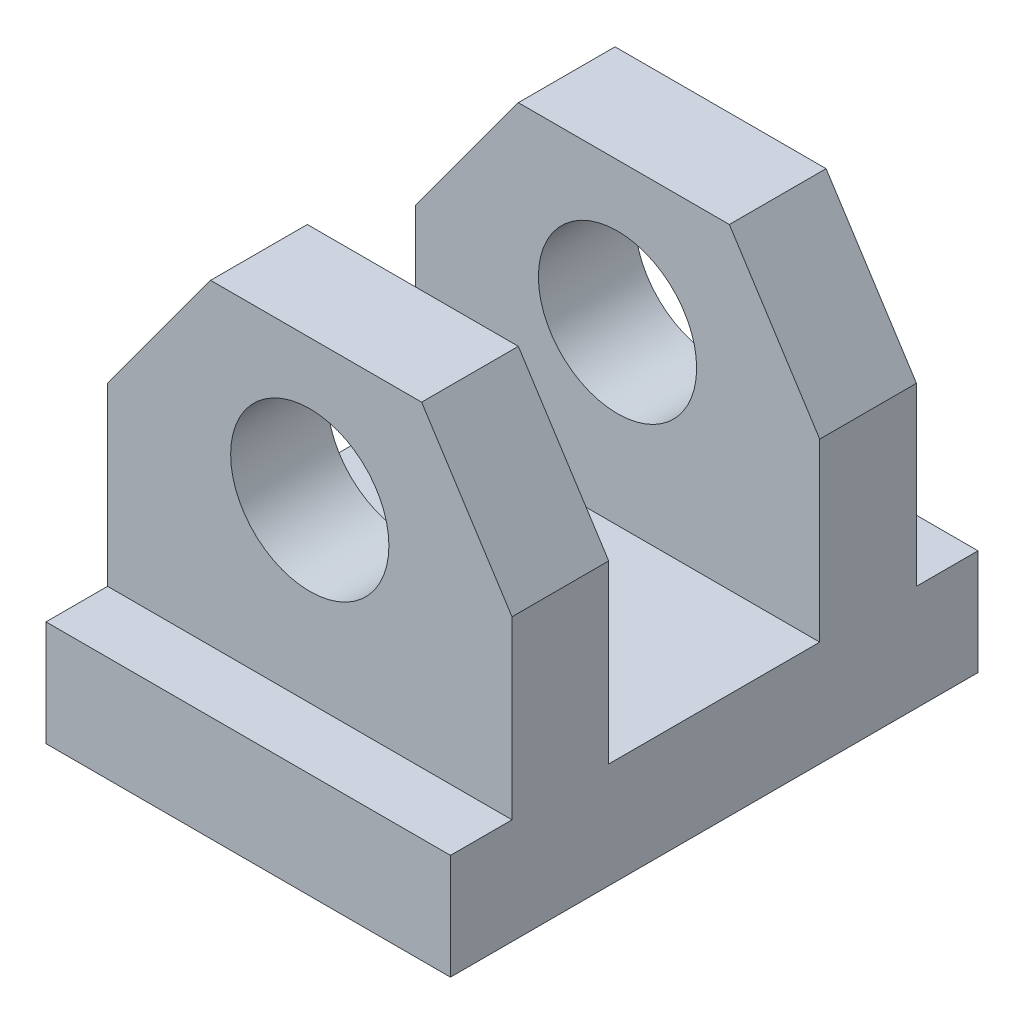
SolidWorks part; units mm, degrees
ref_plane "Alzado" through (0, 0, 0) normal (0, 0, 1) x (1, 0, 0)
ref_plane "Planta" through (0, 0, 0) normal (0, 1, 0) x (1, 0, 0)
ref_plane "Vista lateral" through (0, 0, 0) normal (1, 0, 0) x (0, 0, -1)
sketch "Croquis1" plane through (0, 0, 0) normal (0, 0, 1) x (1, 0, 0)
  line L0 (-23, 0) -> (23, 0)
  line L1 (23, 0) -> (23, 32)
  line L2 (-23, 0) -> (-23, 32)
  line L3 (-23, 32) -> (-11.2791, 48)
  line L4 (-11.2791, 48) -> (12.7209, 48)
  line L5 (12.7209, 48) -> (23, 32)
  circle A0 centre (0, 32) radius 9
  point P4 (0, 0)
  dimension "D4" = 18
  dimension "D1" = 32
  dimension "D2" = 48
  dimension "D3" = 46
  dimension "D5" = 24
extrude "Saliente-Extruir1" add sketch "Croquis1" against normal blind 60
sketch "Croquis3" plane through (0, 48, 0) normal (0, 1, 0) x (1, 0, 0)
  line L0 (23, 60) -> (23, 0) construction
  line L1 (-23, 0) -> (23, 0)
  line L2 (-23, 0) -> (-23, 7)
  line L3 (-23, 7) -> (23, 7)
  line L4 (23, 0) -> (23, 7)
  line L5 (-23, 0) -> (23, 7) construction
  line L6 (-23, 7) -> (23, 0) construction
  line L8 (-23, 60) -> (23, 60)
  line L9 (-23, 60) -> (-23, 53)
  line L10 (-23, 53) -> (23, 53)
  line L11 (23, 60) -> (23, 53)
  line L12 (-23, 60) -> (23, 53) construction
  line L13 (-23, 53) -> (23, 60) construction
  point P4 (0, 3.5)
  point P12 (0, 56.5)
  dimension "D1" = 7
extrude "Cortar-Extruir1" cut sketch "Croquis3" against normal blind 36
sketch "Croquis4" plane through (0, 48, 0) normal (0, 1, 0) x (1, 0, 0)
  line L7 (24.6073, 18) -> (-23, 18)
  line L8 (24.6073, 18) -> (24.6073, 42)
  line L11 (24.6073, 42) -> (-23, 42)
  line L12 (-23, 18) -> (-23, 42)
  line L13 (-23, 53) -> (-23, 7) construction
  point P4 (0.8024, 23.9479)
  point P7 (-23, 30)
  point P8 (-23, 30)
extrude "Cortar-Extruir5" cut sketch "Croquis4" against normal blind 36
